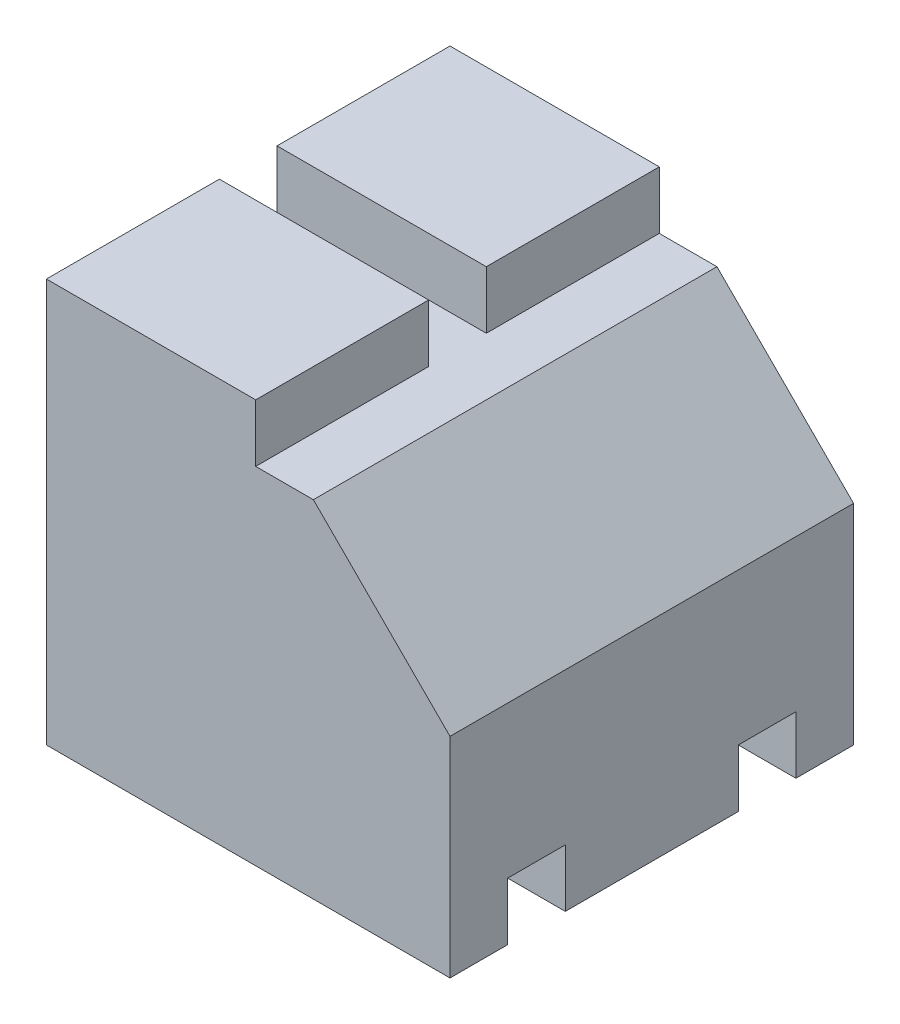
SolidWorks part; units mm, degrees
ref_plane "Alzado" through (0, 0, 0) normal (0, 0, 1) x (1, 0, 0)
ref_plane "Planta" through (0, 0, 0) normal (0, 1, 0) x (1, 0, 0)
ref_plane "Vista lateral" through (0, 0, 0) normal (1, 0, 0) x (0, 0, -1)
sketch "Croquis1" plane through (0, 0, 0) normal (1, 0, 0) x (0, 0, -1)
  line L1 (0, 0) -> (-70, 0)
  line L2 (0, 0) -> (0, 70)
  line L3 (0, 70) -> (-70, 70)
  line L4 (-70, 0) -> (-70, 70)
  dimension "D1" = 70
  dimension "D2" = 70
extrude "Saliente-Extruir1" add sketch "Croquis1" along normal blind 70
sketch "Croquis2" plane through (0, 0, 70) normal (0, 0, 1) x (1, 0, 0)
  line L0 (36.3, 70) -> (70, 36.3)
  line L1 (70, 70) -> (0, 70) construction
  line L2 (70, 70) -> (70, 0) construction
  dimension "D1" = 45
extrude "Cortar-Extruir1" cut sketch "Croquis2" against normal blind 70 and the other way through all
sketch "Croquis3" plane through (70, 0, 0) normal (1, 0, 0) x (0, 0, -1)
  line L0 (-70, 0) -> (0, 0) construction
  line L1 (-20, 0) -> (-10, 0)
  line L2 (-20, 0) -> (-20, 10)
  line L3 (-20, 10) -> (-10, 10)
  line L4 (-10, 0) -> (-10, 10)
  line L5 (-70, 36.3) -> (-70, 0) construction
  line L6 (-50, 0) -> (-60, 0)
  line L7 (-50, 0) -> (-50, 10)
  line L8 (-50, 10) -> (-60, 10)
  line L9 (-60, 0) -> (-60, 10)
  dimension "D1" = 10
  dimension "D2" = 10
  dimension "D3" = 10
  dimension "D4" = 10
  dimension "D5" = 10
  dimension "D6" = 10
extrude "Cortar-Extruir2" cut sketch "Croquis3" against normal blind 70
sketch "Croquis4" plane through (0, 0, 70) normal (0, 0, 1) x (1, 0, 0)
  line L0 (36.3, 70) -> (36.3, 60)
  line L1 (36.3, 70) -> (0, 70) construction
  line L2 (36.3, 60) -> (46.3, 60)
  line L3 (70, 36.3) -> (36.3, 70) construction
  dimension "D1" = 10
  dimension "D2" = 10
extrude "Cortar-Extruir3" cut sketch "Croquis4" against normal through all both and the other way through all
sketch "Croquis5" plane through (36.3, 0, 0) normal (1, 0, 0) x (0, 0, -1)
  line L0 (-70, 70) -> (0, 70) construction
  line L1 (-40, 70) -> (-30, 70)
  line L2 (-40, 70) -> (-40, 60)
  line L3 (-40, 60) -> (-30, 60)
  line L4 (-30, 70) -> (-30, 60)
  line L5 (-70, 60) -> (0, 60) construction
  dimension "D1" = 10
  dimension "D2" = 30
extrude "Cortar-Extruir4" cut sketch "Croquis5" against normal through all both
